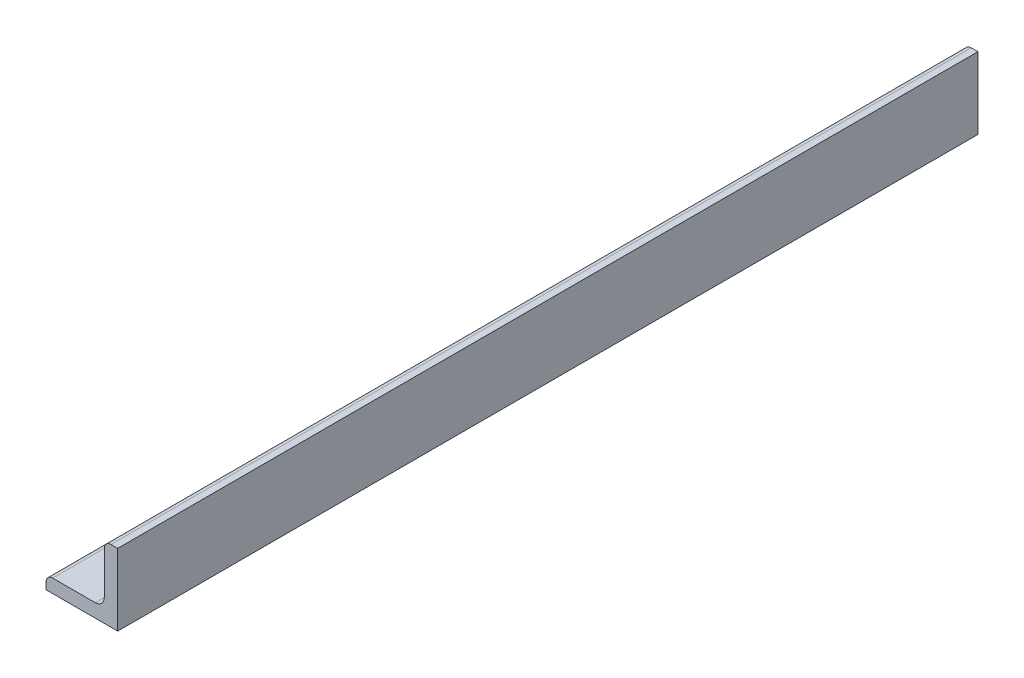
SolidWorks part; units mm, degrees
ref_plane "Front Plane" through (0, 0, 0) normal (0, 0, 1) x (1, 0, 0)
ref_plane "Top Plane" through (0, 0, 0) normal (0, 1, 0) x (1, 0, 0)
ref_plane "Right Plane" through (0, 0, 0) normal (1, 0, 0) x (0, 0, -1)
sketch "Sketch2" plane through (0, 0, 0) normal (0, 0, 1) x (1, 0, 0)
  line L0 (-12.7, 0) -> (12.7, 0)
  line L1 (12.7, 0) -> (12.7, 25.4)
  line L2 (12.7, 25.4) -> (7.9375, 25.4) construction
  line L3 (7.9375, 23.0188) -> (7.9375, 7.9375)
  line L4 (4.7625, 4.7625) -> (-10.3187, 4.7625)
  line L5 (-12.7, 0) -> (-12.7, 4.7625) construction
  line L6 (10.3187, 25.4) -> (12.7, 25.4)
  line L7 (-12.7, 2.3812) -> (-12.7, 0)
  arc A0 (7.9375, 23.0188) -> (10.3187, 25.4) centre (10.3187, 23.0188) cw
  arc A1 (-12.7, 2.3812) -> (-10.3187, 4.7625) centre (-10.3187, 2.3812) cw
  arc A2 (7.9375, 7.9375) -> (4.7625, 4.7625) centre (4.7625, 7.9375) cw
  dimension "Inside Radius" = 3.175
  dimension "Vert" = 25.4
  dimension "Horz" = 25.4
  dimension "Thickness" = 4.7625
extrude "Boss-Extrude1" add sketch "Sketch2" along normal mid plane 304.8
sketch "Break Locations" plane through (0, 0, 0) normal (1, 0, 0) x (0, 0, -1)
  line L1 (-152.4, 0) -> (-152.4, 25.4) construction
  line L2 (152.4, 0) -> (152.4, 25.4) construction
  point P0 (-130.81, 0)
  point P1 (130.81, 0)
  dimension "D1" = 21.59
  dimension "D2" = 21.59
ref_plane "Contact Plane 1" through (0, 4.7625, 0) normal (0, 1, 0) x (1, 0, 0)
ref_plane "Contact Plane 2" through (7.9375, 0, 0) normal (-1, 0, 0) x (0, 0, 1)
equation "\"D1@Break Locations\"=.85*\"Vert@Sketch2\""
equation "\"D2@Break Locations\"=\"D1@Break Locations\""
